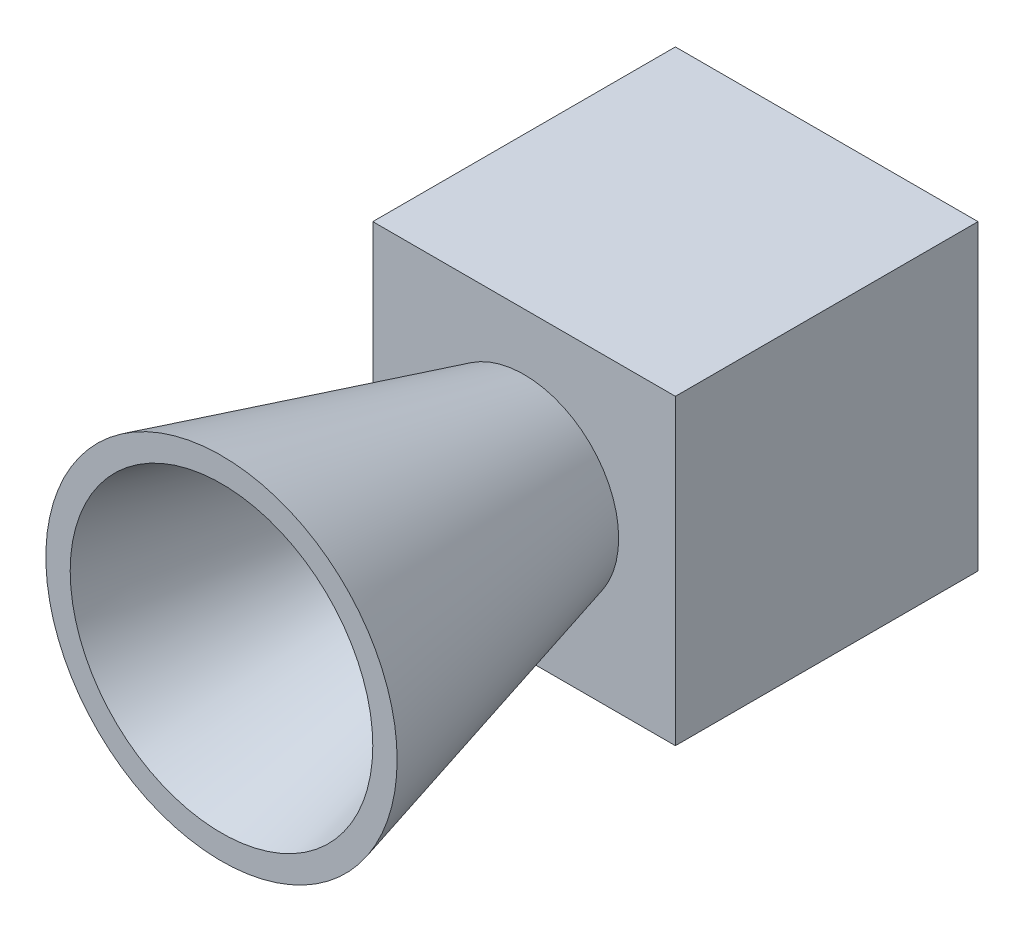
SolidWorks part; units mm, degrees
material "Plain Carbon Steel"
ref_plane "Front Plane" through (0, 0, 0) normal (0, 0, 1) x (1, 0, 0)
ref_plane "Top Plane" through (0, 0, 0) normal (0, 1, 0) x (1, 0, 0)
ref_plane "Right Plane" through (0, 0, 0) normal (1, 0, 0) x (0, 0, -1)
sketch "Sketch1" plane through (0, 0, 0) normal (0, 0, 1) x (1, 0, 0)
  line L1 (609.6, -609.6) -> (-609.6, -609.6)
  line L2 (609.6, -609.6) -> (609.6, 609.6)
  line L3 (609.6, 609.6) -> (-609.6, 609.6)
  line L4 (-609.6, -609.6) -> (-609.6, 609.6)
  line L5 (609.6, -609.6) -> (-609.6, 609.6) construction
  line L6 (609.6, 609.6) -> (-609.6, -609.6) construction
  point P0 (0, 0)
  dimension "D1" = 1219.2
extrude "Boss-Extrude1" add sketch "Sketch1" along normal blind 1219.2
sketch "Sketch2" plane through (0, 0, 1219.2) normal (0, 0, 1) x (1, 0, 0)
  circle A0 centre (0, 0) radius 381
  dimension "D1" = 762
extrude "Boss-Extrude2" add sketch "Sketch2" along normal blind 1219.2 draft 15 draft outward yes
sketch "Sketch3" plane through (0, 0, 2438.4) normal (0, 0, 1) x (1, 0, 0)
  circle A0 centre (0, 0) radius 609.6
  dimension "D1" = 1219.2
extrude "Cut-Extrude1" cut sketch "Sketch3" against normal blind 1219.2 draft 15
sketch "Sketch4" plane through (0, 0, 0) normal (0, 0, -1) x (-1, 0, 0)
  line L1 (533.4, -533.4) -> (-533.4, -533.4)
  line L2 (533.4, -533.4) -> (533.4, 533.4)
  line L3 (533.4, 533.4) -> (-533.4, 533.4)
  line L4 (-533.4, -533.4) -> (-533.4, 533.4)
  line L5 (533.4, -533.4) -> (-533.4, 533.4) construction
  line L6 (533.4, 533.4) -> (-533.4, -533.4) construction
  point P0 (0, 0)
  dimension "D1" = 1066.8
extrude "Cut-Extrude2" cut sketch "Sketch4" along direction (0, 0, -1) on the side against the normal blind 1066.8 from offset 38.1 offset against normal yes
